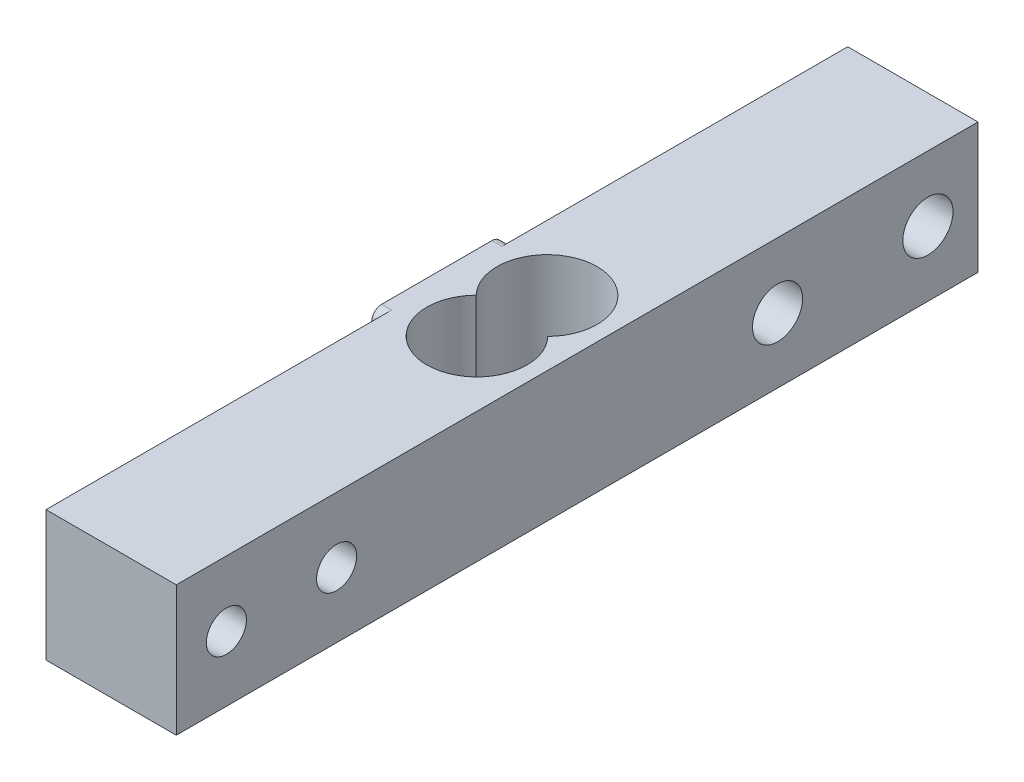
SolidWorks part; units mm, degrees
material "1060 Alloy"
ref_plane "Front Plane" through (0, 0, 0) normal (0, 0, 1) x (1, 0, 0)
ref_plane "Top Plane" through (0, 0, 0) normal (0, 1, 0) x (1, 0, 0)
ref_plane "Right Plane" through (0, 0, 0) normal (1, 0, 0) x (0, 0, -1)
sketch "Sketch1" plane through (0, 0, 0) normal (0, 0, 1) x (1, 0, 0)
  line L1 (-6.5, 6.5) -> (6.5, 6.5)
  line L2 (-6.5, 6.5) -> (-6.5, -6.5)
  line L3 (-6.5, -6.5) -> (6.5, -6.5)
  line L4 (6.5, 6.5) -> (6.5, -6.5)
  line L5 (-6.5, 6.5) -> (6.5, -6.5) construction
  line L6 (-6.5, -6.5) -> (6.5, 6.5) construction
  point P0 (0, 0)
  dimension "D1" = 13
extrude "Boss-Extrude1" add sketch "Sketch1" along normal mid plane 80
sketch "Sketch2" plane through (0, 6.5, 0) normal (0, 1, 0) x (1, 0, 0)
  line L0 (0, -3.5) -> (0, 3.5) construction
  arc A0 (3.5707, 0) -> (-3.5707, 0) centre (0, 3.5) ccw
  arc A1 (-3.5707, 0) -> (3.5707, 0) centre (0, -3.5) ccw
  point P6 (-0.144, 3.5)
  dimension "D2" = 10
  dimension "D3" = 10
  dimension "D1" = 7
extrude "Cut-Extrude1" cut sketch "Sketch2" against normal through all
sketch "Sketch3" plane through (6.5, 0, 0) normal (1, 0, 0) x (0, 0, -1)
  line L0 (-40, 0) -> (40, 0) construction
  line L1 (-40, -6.5) -> (-40, 6.5) construction
  line L2 (40, -6.5) -> (40, 6.5) construction
  circle A0 centre (-35, 0) radius 2
  circle A1 centre (-24, 0) radius 2
  circle A2 centre (20, 0) radius 2.5
  circle A3 centre (35, 0) radius 2.5
  point P14 (33.0412, 0)
  dimension "D1" = 4
  dimension "D2" = 4
  dimension "D3" = 5
  dimension "D4" = 5
  dimension "D5" = 11
  dimension "D6" = 5
  dimension "D7" = 15
  dimension "D8" = 5
extrude "Cut-Extrude2" cut sketch "Sketch3" against normal through all
sketch "Sketch5" plane through (-6.5, 0, 0) normal (-1, 0, 0) x (0, 0, 1)
  line L0 (40, -6.5) -> (-40, -6.5) construction
  line L1 (-6.5, 6.5) -> (6.5, 6.5)
  line L2 (-6.5, 6.5) -> (-6.5, -6.5)
  line L3 (-6.5, -6.5) -> (6.5, -6.5)
  line L4 (6.5, 6.5) -> (6.5, -6.5)
  line L5 (-6.5, 6.5) -> (6.5, -6.5) construction
  line L6 (-6.5, -6.5) -> (6.5, 6.5) construction
  point P0 (0, 0)
  dimension "D1" = 13
extrude "Boss-Extrude2" add sketch "Sketch5" along normal blind 1
fillet "Fillet1" radius 1 4 edges at (-7, -6.5, 6.5) (-7, 6.5, 6.5) (-7, 6.5, -6.5) (-7, -6.5, -6.5)
